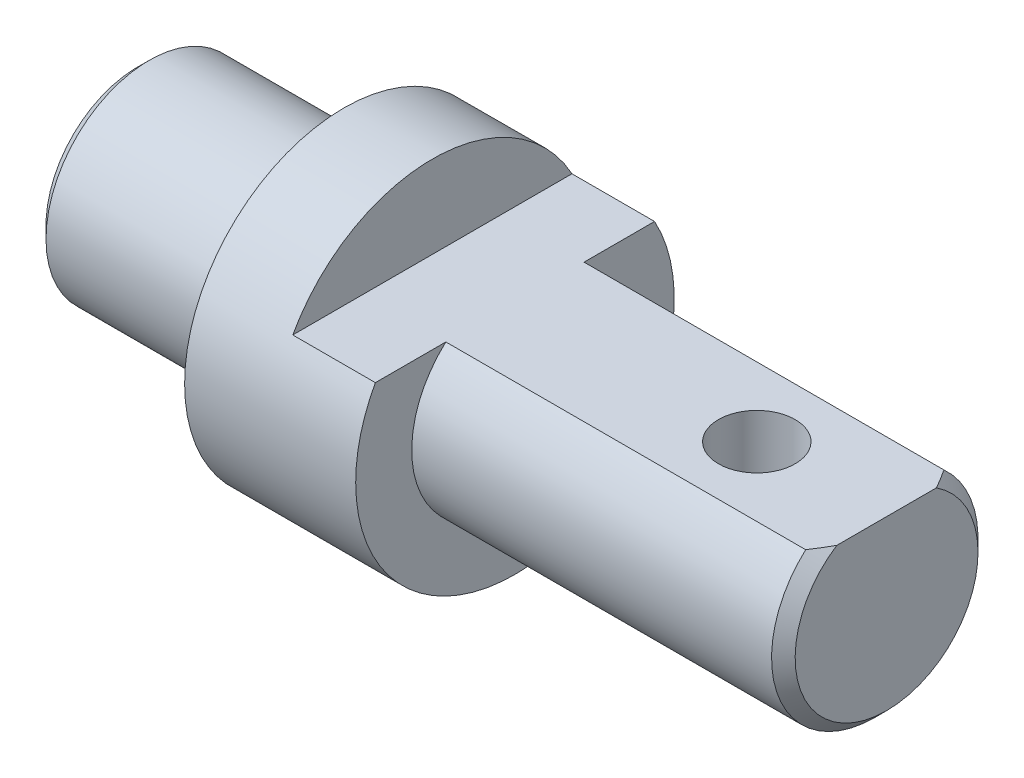
SolidWorks part; units mm, degrees
ref_plane "Front Plane" through (0, 0, 0) normal (0, 0, 1) x (1, 0, 0)
ref_plane "Top Plane" through (0, 0, 0) normal (0, 1, 0) x (1, 0, 0)
ref_plane "Right Plane" through (0, 0, 0) normal (1, 0, 0) x (0, 0, -1)
sketch "Sketch2" plane through (0, 0, 0) normal (0, 0, 1) x (1, 0, 0)
  line L0 (-63.5, 0) -> (-63.5, 17.5)
  line L1 (-63.5, 17.5) -> (-28.5, 17.5)
  line L2 (-28.5, 17.5) -> (-28.5, 27)
  line L3 (-28.5, 27) -> (0.5, 27)
  line L4 (0.5, 27) -> (0.5, 17.5)
  line L5 (0.5, 17.5) -> (63.5, 17.5)
  line L6 (-63.5, 0) -> (63.5, 0)
  line L7 (63.5, 0) -> (63.5, 17.5)
  line L8 (55, 0) -> (-55, 0) construction
  line L9 (0, -55) -> (0, 55) construction
  line L10 (-63.5, 0) -> (63.5, 0) construction
  point P10 (0, 0)
  dimension "D1" = 17.5
  dimension "D2" = 35
  dimension "D3" = 29
  dimension "D4" = 127
  dimension "D5" = 9.5
  dimension "D6" = 9.5
revolve "Revolve1" add sketch "Sketch2" angle 360 about L10
sketch "Sketch4" plane through (0, 0, 0) normal (0, 0, 1) x (1, 0, 0)
  line L0 (-28.5, 17.5) -> (-31.5, 17.5)
  line L1 (-28.5, 17.5) -> (-63.5, 17.5) construction
  line L2 (-31.5, 17.5) -> (-31.5, 16.5)
  line L3 (-31.5, 16.5) -> (-28.5, 16.5)
  line L4 (-28.5, 17.5) -> (-28.5, -17.5) construction
  line L5 (-28.5, 16.5) -> (-28.5, 17.5)
  line L6 (-63.5, 0) -> (-28.5, 0) construction
  line L7 (-63.5, 17.5) -> (-63.5, -17.5) construction
  dimension "D1" = 3
  dimension "D2" = 1
revolve "Cut-Revolve1" cut sketch "Sketch4" angle 360 about L6
sketch "Sketch5" plane through (63.5, 0, 0) normal (1, 0, 0) x (0, 0, -1)
  line L0 (-23.6643, 13) -> (23.6643, 13)
  line L1 (23.6643, 13) -> (23.6643, 27)
  line L2 (23.6643, 27) -> (-23.6643, 27)
  line L3 (-23.6643, 27) -> (-23.6643, 13)
  line L4 (29.7, 0) -> (-29.7, 0) construction
  circle A0 centre (0, 0) radius 27 construction
  dimension "D1" = 13
extrude "Cut-Extrude1" cut sketch "Sketch5" against normal blind 77
hole_wizard "1/2 (0.51181102) Dowel Hole1" positions "Sketch6" profile "Sketch7" hole size "1/2" standard "ANSI Inch" end condition through all
sketch "Sketch6" plane through (0, 13, 0) normal (0, 1, 0) x (1, 0, 0)
  line L0 (-29.7, 0) -> (29.7, 0) construction
  line L1 (63.5, -11.7154) -> (63.5, 11.7154) construction
  point P0 (41.5, 0)
  dimension "D1" = 22
sketch "Sketch7" plane through (41.5, 13, 0) normal (1, 0, 0) x (0, 0, 1)
  line L0 (0, 0) -> (0, 40)
  line L1 (0, 40) -> (6.5, 40)
  line L2 (6.5, 40) -> (6.5, 0)
  line L5 (6.5, 0) -> (0, 0)
  line L11 (0, -6.35) -> (0, 107.95) construction
  dimension "Thru Hole Dia." = 13
  dimension "Thru Hole Depth" = 40
chamfer "Chamfer1" distance 2 angle 45 2 edges at (63.5, -17.5, 0) (-63.5, 0, 17.5)
